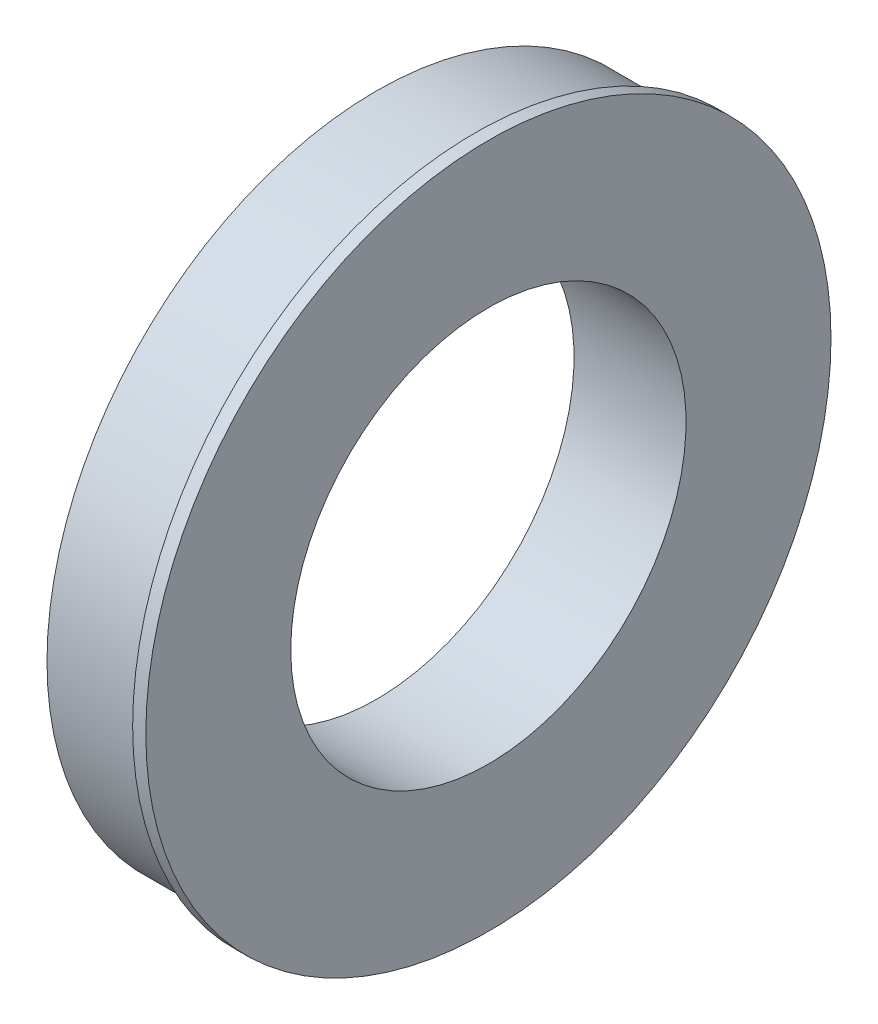
SolidWorks part; units mm, degrees
ref_plane "Front Plane" through (0, 0, 0) normal (0, 0, 1) x (1, 0, 0)
ref_plane "Top Plane" through (0, 0, 0) normal (0, 1, 0) x (1, 0, 0)
ref_plane "Right Plane" through (0, 0, 0) normal (1, 0, 0) x (0, 0, -1)
sketch "Sketch1" plane through (0, 0, 0) normal (1, 0, 0) x (0, 0, -1)
  circle A0 centre (0, 0) radius 38.1
  circle A1 centre (0, 0) radius 63.5
  dimension "D1" = 76.2
  dimension "D2" = 127
extrude "Boss-Extrude1" add sketch "Sketch1" along normal blind 19.05
sketch "Sketch2" plane through (19.05, 0, 0) normal (1, 0, 0) x (0, 0, -1)
  circle A0 centre (0, 0) radius 38.1 construction
  circle A1 centre (0, 0) radius 38.1
  circle A4 centre (0, 0) radius 66.04
  circle A5 centre (0, 0) radius 66.04
  dimension "D1" = 2.54
extrude "Boss-Extrude2" add sketch "Sketch2" along normal blind 2.54
